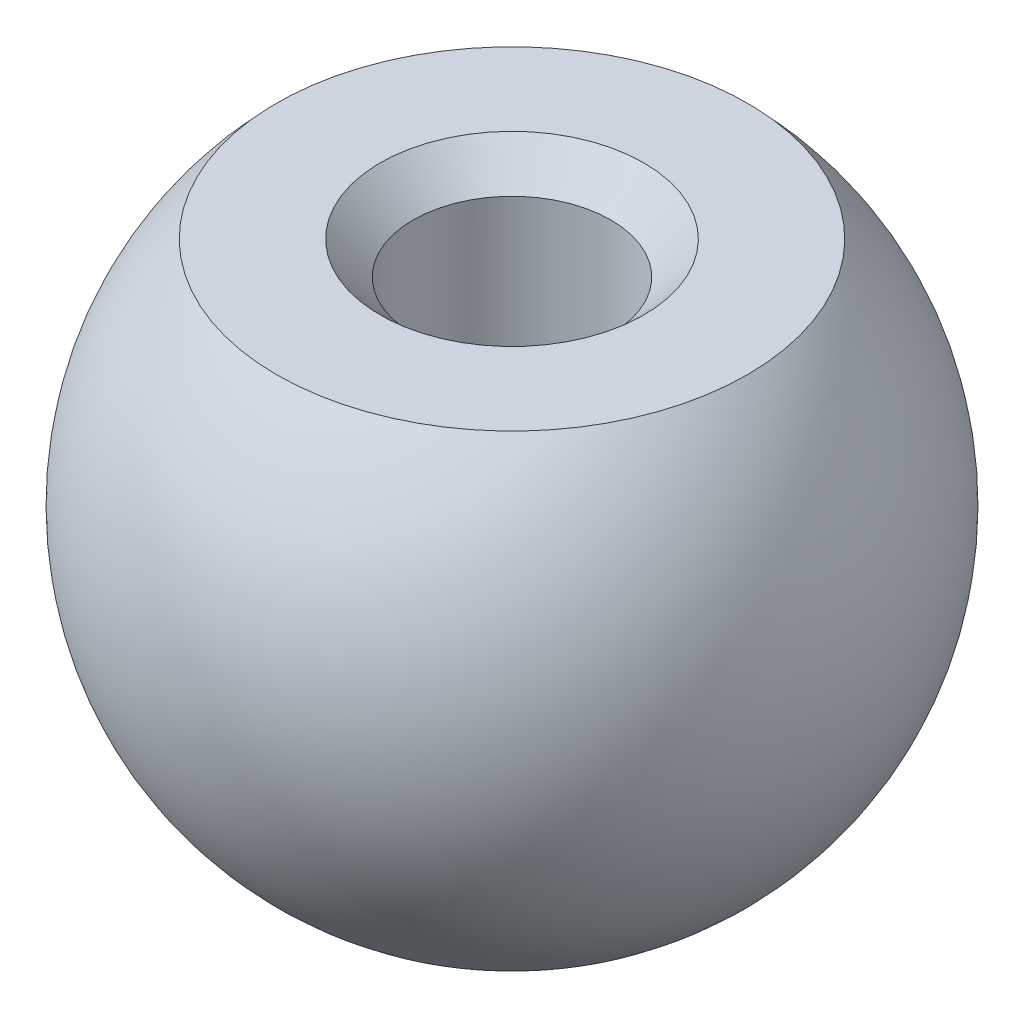
SolidWorks part; units mm, degrees
ref_plane "Piano frontale" through (0, 0, 0) normal (0, 0, 1) x (1, 0, 0)
ref_plane "Piano superiore" through (0, 0, 0) normal (0, 1, 0) x (1, 0, 0)
ref_plane "Piano destro" through (0, 0, 0) normal (1, 0, 0) x (0, 0, -1)
sketch "Schizzo1" plane through (0, 0, 0) normal (0, 0, 1) x (1, 0, 0)
  line L0 (0, 5) -> (0, -5) construction
  line L1 (0, 5) -> (0, -5)
  arc A0 (0, 5) -> (0, -5) centre (0, 0) ccw
  dimension "D1" = 10
revolve "Rivoluzione1" add sketch "Schizzo1" angle 360 about L0
ref_plane "Piano1" through (0, 3.5, 0) normal (0, 1, 0) x (1, 0, 0)
sketch "Schizzo2" plane through (0, 0, 0) normal (0, 0, 1) x (1, 0, 0)
  line L0 (0, 5) -> (0, 0) construction
  line L1 (0, 3.5) -> (-3.5707, 3.5)
  line L2 (5.5, 3.5) -> (-5.5, 3.5) construction
  line L3 (0, 5) -> (0, 3.5)
  arc A0 (0, 5) -> (-3.5707, 3.5) centre (0, 0) ccw
  point P1 (0, 0)
  dimension "D1" = 10
revolve "Taglia-Rivoluzione1" cut sketch "Schizzo2" angle 360 about L0
sketch "Schizzo3" plane through (0, 3.5, 0) normal (0, 1, 0) x (1, 0, 0)
  circle A0 centre (0, 0) radius 1.5
  dimension "D1" = 3
extrude "Taglio-Estrusione1" cut sketch "Schizzo3" against normal blind 6
chamfer "Smusso1" distance 0.5 angle 45 1 edges at (0, 3.5, 1.5)
